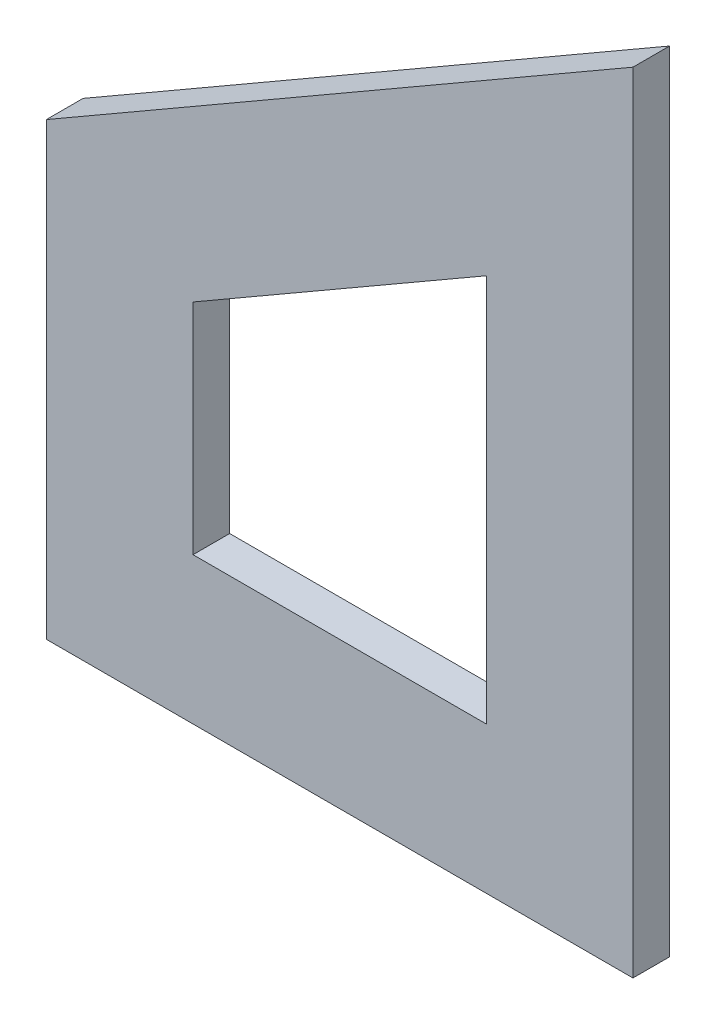
SolidWorks part; units mm, degrees
ref_plane "Front Plane" through (0, 0, 0) normal (0, 0, 1) x (1, 0, 0)
ref_plane "Top Plane" through (0, 0, 0) normal (0, 1, 0) x (1, 0, 0)
ref_plane "Right Plane" through (0, 0, 0) normal (1, 0, 0) x (0, 0, -1)
sketch "Sketch1" plane through (0, 0, 0) normal (0, 0, 1) x (1, 0, 0)
  line L0 (-130.8385, 95.25) -> (-29.2385, 95.25)
  line L1 (165.3114, 95.25) -> (-69.85, 95.25) construction
  line L2 (-29.2385, 95.25) -> (-29.2385, 231.8816)
  line L3 (-29.2385, 231.8816) -> (-130.8385, 173.2228)
  line L4 (-130.8385, 173.2228) -> (-130.8385, 95.25)
  line L5 (-130.8385, 173.2228) -> (-71.8403, 173.2228) construction
  line L6 (-130.8385, 173.2228) -> (-215.9, 124.1125) construction
  line L7 (0, -28.2875) -> (-285.4435, -28.2875) construction
  line L8 (-215.9, 95.25) -> (-215.9, 88.9) construction
  circle A0 centre (0, 20.925) radius 49.2125 construction
  dimension "D1" = 30
  dimension "D2" = 101.6
  dimension "D3" = 152.4
extrude "Boss-Extrude1" add sketch "Sketch1" along normal mid plane 6.35
sketch "Sketch2" plane through (0, 0, 3.175) normal (0, 0, 1) x (1, 0, 0)
  line L14 (-54.6385, 120.65) -> (-54.6385, 187.8875)
  line L15 (-105.4385, 120.65) -> (-54.6385, 120.65)
  line L16 (-105.4385, 158.5581) -> (-105.4385, 120.65)
  line L17 (-54.6385, 187.8875) -> (-105.4385, 158.5581)
  line L18 (-54.6385, 120.65) -> (-54.6385, 187.8875)
  line L19 (-105.4385, 120.65) -> (-54.6385, 120.65)
  line L20 (-105.4385, 158.5581) -> (-105.4385, 120.65)
  line L21 (-54.6385, 187.8875) -> (-105.4385, 158.5581)
  dimension "D1" = 25.4
extrude "Cut-Extrude1" cut sketch "Sketch2" against normal through all
